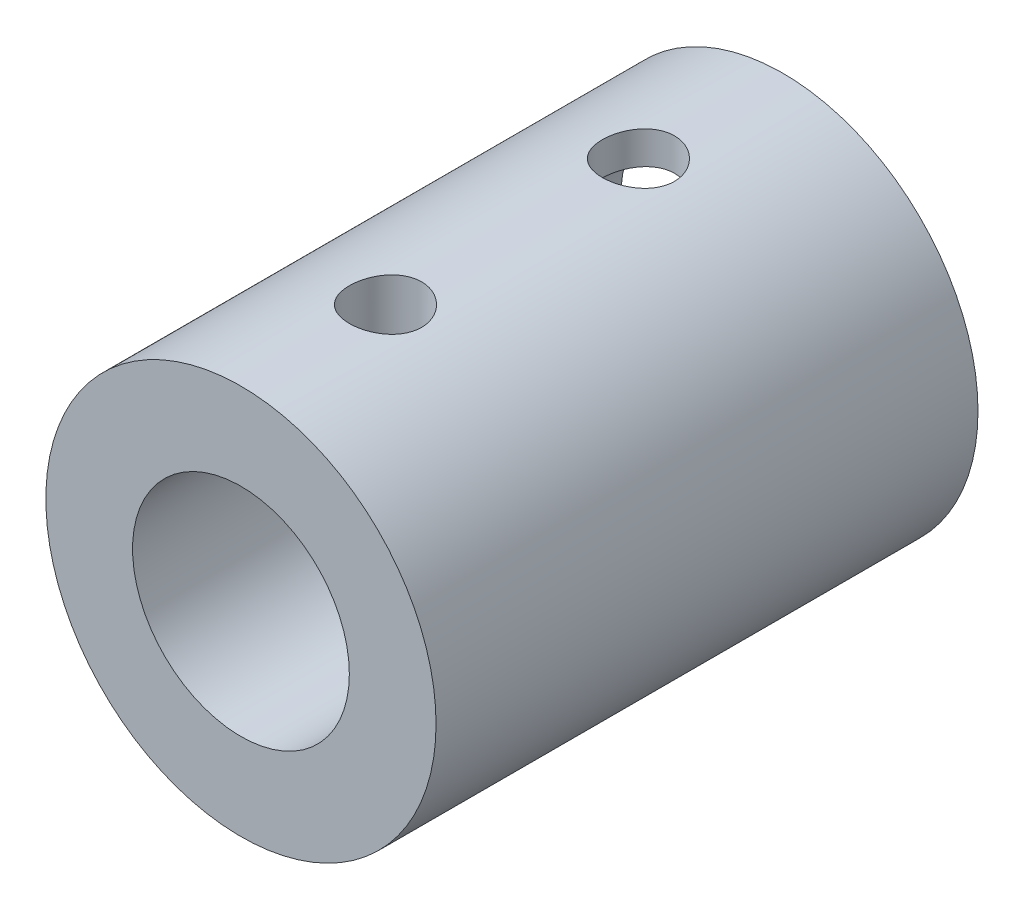
SolidWorks part; units mm, degrees
ref_plane "Front Plane" through (0, 0, 0) normal (0, 0, 1) x (1, 0, 0)
ref_plane "Top Plane" through (0, 0, 0) normal (0, 1, 0) x (1, 0, 0)
ref_plane "Right Plane" through (0, 0, 0) normal (1, 0, 0) x (0, 0, -1)
sketch "Croquis1" plane through (0, 0, 0) normal (0, 1, 0) x (1, 0, 0)
  line L0 (0, -7.5) -> (0, 0)
  line L1 (0, 0) -> (0, 7.5)
  line L2 (0, 7.5) -> (5.4, 7.5)
  line L3 (5.4, 7.5) -> (5.4, -7.5)
  line L4 (0, -7.5) -> (5.4, -7.5)
  line L5 (0, 0) -> (0, 14.6716) construction
  dimension "D1" = 5.4
  dimension "D2" = 7.5
  dimension "D3" = 7.5
revolve "Revolución1" add sketch "Croquis1" angle 360 about L5
sketch "Croquis2" plane through (0, 0, 0) normal (0, 1, 0) x (1, 0, 0)
  line L0 (0, 0) -> (0, -3.5) construction
  line L1 (0, 0) -> (3.0052, 0) construction
  circle A0 centre (0, -3.5) radius 1
  circle A1 centre (0, 3.5) radius 1
  dimension "D2" = 2
  dimension "D1" = 3.5
extrude "Cortar-Extruir1" cut sketch "Croquis2" along normal blind 10
sketch "Croquis3" plane through (0, 0, 7.5) normal (0, 0, 1) x (1, 0, 0)
  circle A0 centre (0, 0) radius 3
  dimension "D1" = 6
extrude "Cortar-Extruir2" cut sketch "Croquis3" against normal blind 7.5
sketch "Croquis4" plane through (0, 0, -7.5) normal (0, 0, -1) x (-1, 0, 0)
  circle A0 centre (0, 0) radius 4.5
  dimension "D1" = 9
extrude "Cortar-Extruir3" cut sketch "Croquis4" against normal blind 7.5
